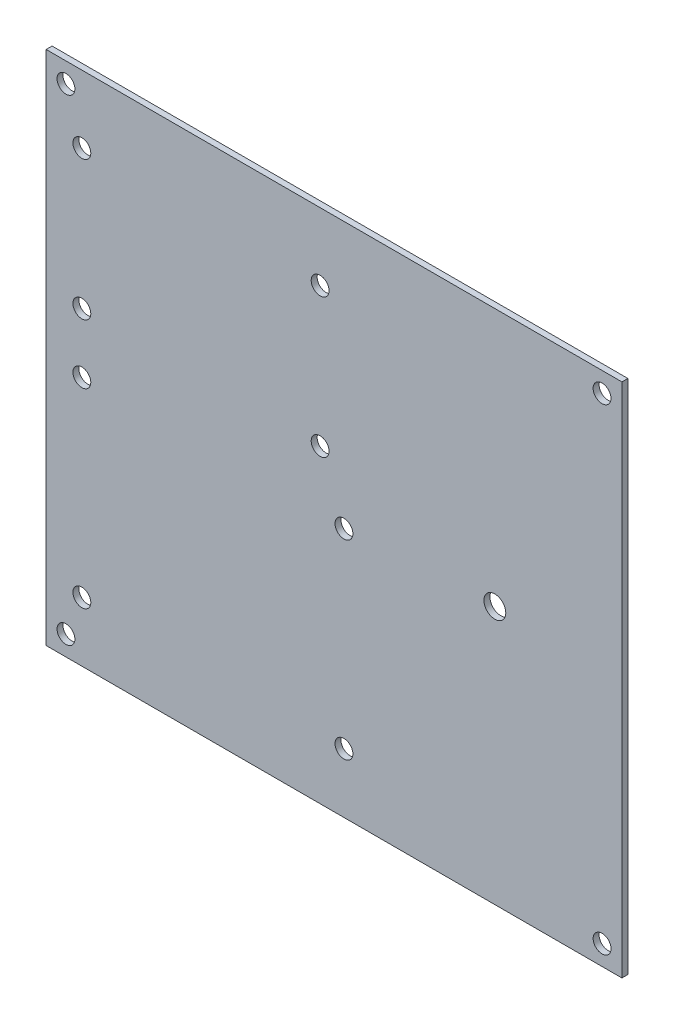
SolidWorks part; units mm, degrees
ref_plane "Спереди" through (0, 0, 0) normal (0, 0, 1) x (1, 0, 0)
ref_plane "Сверху" through (0, 0, 0) normal (0, 1, 0) x (1, 0, 0)
ref_plane "Справа" through (0, 0, 0) normal (1, 0, 0) x (0, 0, -1)
sketch "Эскиз1" plane through (0, 0, 0) normal (0, 0, 1) x (1, 0, 0)
  line L0 (0, 42.3611) -> (0, -41.9385) construction
  line L1 (-56.8336, 0) -> (57.0449, 0) construction
  line L2 (2.5, -50) -> (2.5, -2) construction
  line L3 (-72.5, -65) -> (72.5, -65)
  line L4 (-72.5, -65) -> (-72.5, 65)
  line L5 (-72.5, 65) -> (72.5, 65)
  line L6 (72.5, -65) -> (72.5, 65)
  line L7 (2.5, -50) -> (-63.5, -50) construction
  circle A0 centre (-67.5, 60) radius 2.25
  circle A1 centre (-67.5, -60) radius 2.25
  circle A2 centre (67.5, -60) radius 2.25
  circle A3 centre (67.5, 60) radius 2.25
  circle A4 centre (-63.5, -2) radius 2.25
  circle A5 centre (-63.5, -50) radius 2.25
  circle A6 centre (2.5, -2) radius 2.25
  circle A7 centre (2.5, -50) radius 2.25
  circle A8 centre (40.5, 0) radius 2.75
  circle A9 centre (-63.5, 13) radius 2.25
  circle A10 centre (-63.5, 48) radius 2.25
  circle A11 centre (-3.5, 13) radius 2.25
  circle A12 centre (-3.5, 48) radius 2.25
  dimension "D3" = 5
  dimension "D5" = 4.5
  dimension "D8" = 4.5
  dimension "D10" = 15
  dimension "D7" = 48
  dimension "D11" = 48
  dimension "D6" = 66
  dimension "D12" = 65
  dimension "D13" = 66
  dimension "D14" = 32
  dimension "D15" = 5.5
  dimension "D16" = 35
  dimension "D17" = 15
  dimension "D19" = 60
  dimension "D20" = 60
  dimension "D21" = 35
  dimension "D22" = 15
  dimension "D1" = 145
  dimension "D2" = 130
  dimension "D4" = 5
  dimension "D9" = 75
  dimension "D18" = 9
  dimension "D23" = 9
extrude "Вытянуть1" add sketch "Эскиз1" along normal blind 1.5
